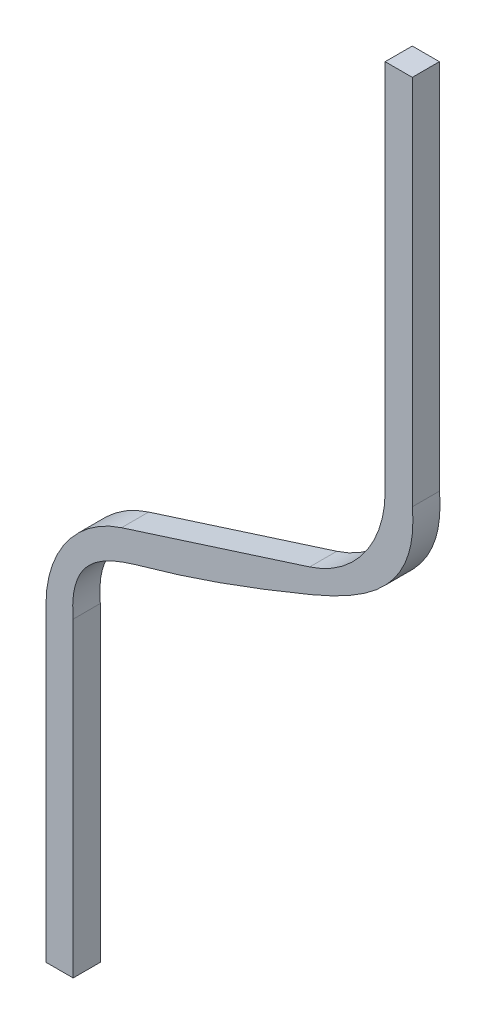
SolidWorks part; units mm, degrees
ref_plane "Plano frontal" through (0, 0, 0) normal (0, 0, 1) x (1, 0, 0)
ref_plane "Plano superior" through (0, 0, 0) normal (0, 1, 0) x (1, 0, 0)
ref_plane "Plano direito" through (0, 0, 0) normal (1, 0, 0) x (0, 0, -1)
sketch "Esboço1" plane through (0, 0, 0) normal (0, 0, 1) x (1, 0, 0)
  line L0 (0, 0) -> (0, 2.291)
  line L1 (2.5, 7) -> (2.5, 4.258)
  line L2 (1.9434, 3.496) -> (0.5566, 3.0531)
  line L3 (2.5, 7) -> (2.7, 7)
  line L4 (2.7, 7) -> (2.7, 4.258)
  line L5 (0, 0) -> (0.2, 0)
  line L6 (0.2, 0) -> (0.2, 2.291)
  arc A0 (0, 2.291) -> (0.5566, 3.0531) centre (0.8, 2.291) cw
  arc A1 (1.9434, 3.496) -> (2.5, 4.258) centre (1.7, 4.258) ccw
  spline S0 degree 3 poles (0.2, 2.291) (0.1587, 2.7464) (0.6619, 2.8589) (1.2988, 3.0651) (2.0661, 3.36) (2.7535, 3.667) (2.7, 4.258) knots 0 0 0 0 0.272333 0.409919 0.591592 1 1 1 1
  dimension "D1" = 0.8
  dimension "D2" = 2.5
  dimension "D3" = 0.2
  dimension "D4" = 0.2
extrude "Ressalto-extrusão1" add sketch "Esboço1" along normal blind 0.2
equation "\".20.00mm\"=20"
